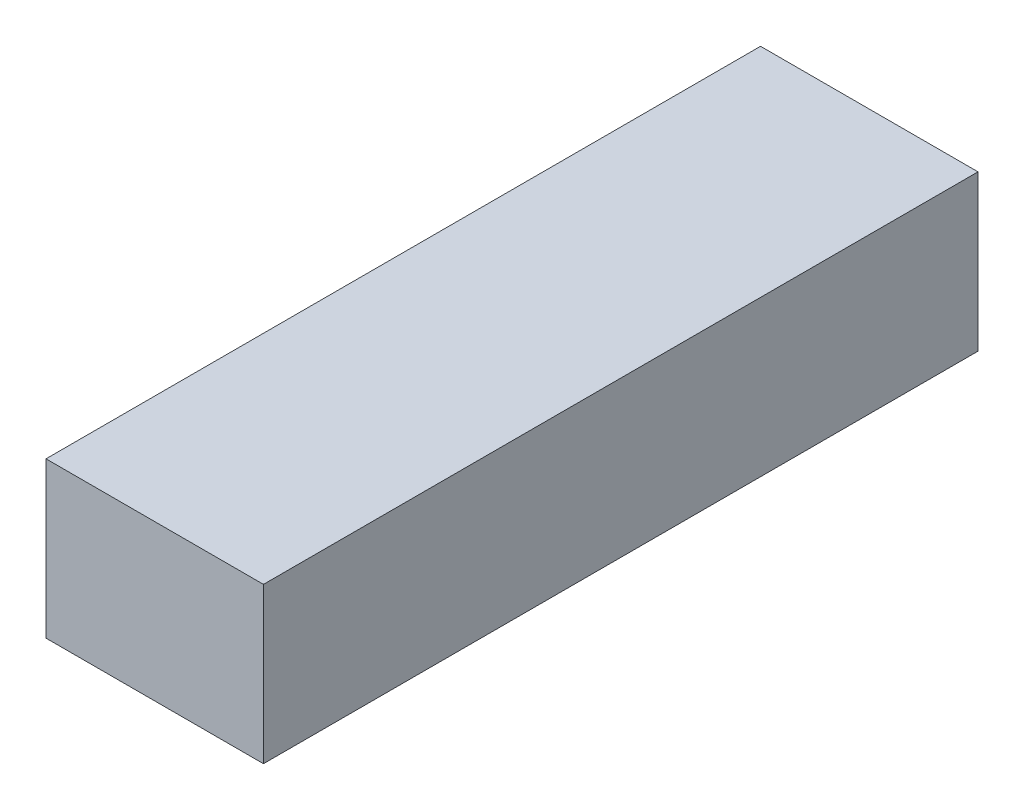
SolidWorks part; units mm, degrees
ref_plane "Front Plane" through (0, 0, 0) normal (0, 0, 1) x (1, 0, 0)
ref_plane "Top Plane" through (0, 0, 0) normal (0, 1, 0) x (1, 0, 0)
ref_plane "Right Plane" through (0, 0, 0) normal (1, 0, 0) x (0, 0, -1)
sketch "Sketch1" plane through (0, 0, 0) normal (0, 1, 0) x (1, 0, 0)
  line L1 (-17.5, 57.5) -> (17.5, 57.5)
  line L2 (-17.5, 57.5) -> (-17.5, -57.5)
  line L3 (-17.5, -57.5) -> (17.5, -57.5)
  line L4 (17.5, 57.5) -> (17.5, -57.5)
  line L5 (-17.5, 57.5) -> (17.5, -57.5) construction
  line L6 (-17.5, -57.5) -> (17.5, 57.5) construction
  point P0 (0, 0)
  dimension "D1" = 115
  dimension "D2" = 35
extrude "Boss-Extrude1" add sketch "Sketch1" along normal blind 25
